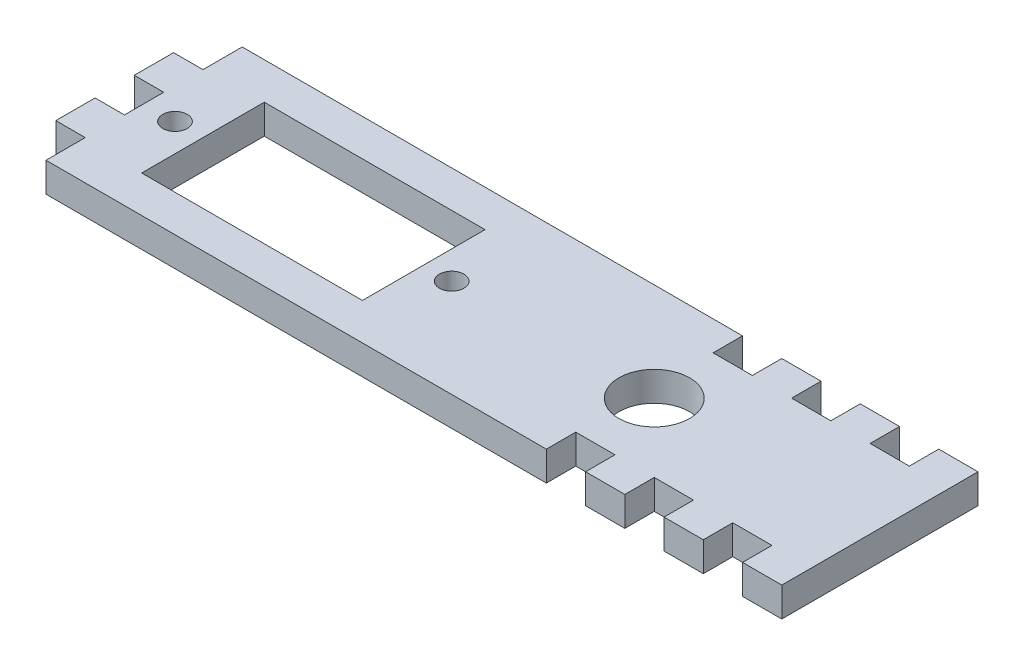
SolidWorks part; units mm, degrees
ref_plane "Alzado" through (0, 0, 0) normal (0, 0, 1) x (1, 0, 0)
ref_plane "Planta" through (0, 0, 0) normal (0, 1, 0) x (1, 0, 0)
ref_plane "Vista lateral" through (0, 0, 0) normal (1, 0, 0) x (0, 0, -1)
sketch "Croquis1" plane through (0, 0, 0) normal (0, 1, 0) x (1, 0, 0)
  line L1 (-37.5, -10) -> (37.5, -10)
  line L2 (-37.5, -10) -> (-37.5, 10)
  line L3 (-37.5, 10) -> (37.5, 10)
  line L4 (37.5, -10) -> (37.5, 10)
  line L5 (-37.5, -10) -> (37.5, 10) construction
  line L6 (-37.5, 10) -> (37.5, -10) construction
  line L14 (-37.5, 2) -> (-37.5, 6)
  line L15 (-37.5, -6) -> (-40.5, -6)
  line L16 (-31.5, 6.25) -> (-9, 6.25)
  line L17 (-31.5, 6.25) -> (-31.5, -6.25)
  line L18 (-31.5, -6.25) -> (-9, -6.25)
  line L19 (-9, 6.25) -> (-9, -6.25)
  line L20 (-31.5, 6.25) -> (-9, -6.25) construction
  line L21 (-31.5, -6.25) -> (-9, 6.25) construction
  line L22 (-37.5, -6) -> (-37.5, -2)
  line L23 (-37.5, -2) -> (-40.5, -2)
  line L24 (-40.5, -6) -> (-40.5, -2)
  line L25 (-37.5, 2) -> (-40.5, 2)
  line L26 (-40.5, 2) -> (-40.5, 6)
  line L27 (-37.5, 6) -> (-40.5, 6)
  line L36 (25.5, -10) -> (25.5, -7)
  line L37 (33.5, -10) -> (29.5, -10)
  line L38 (33.5, -10) -> (33.5, -7)
  line L39 (33.5, -7) -> (29.5, -7)
  line L40 (29.5, -10) -> (29.5, -7)
  line L41 (25.5, -10) -> (21.5, -10)
  line L42 (21.5, -10) -> (21.5, -7)
  line L43 (25.5, -7) -> (21.5, -7)
  line L44 (17.5, -10) -> (17.5, -7)
  line L45 (17.5, -10) -> (13.5, -10)
  line L46 (13.5, -10) -> (13.5, -7)
  line L47 (17.5, -7) -> (13.5, -7)
  line L48 (0, 0) -> (9.9901, 0) construction
  line L49 (33.5, 7) -> (29.5, 7)
  line L50 (29.5, 10) -> (29.5, 7)
  line L51 (33.5, 10) -> (29.5, 10)
  line L52 (33.5, 10) -> (33.5, 7)
  line L53 (25.5, 10) -> (21.5, 10)
  line L54 (21.5, 10) -> (21.5, 7)
  line L55 (25.5, 7) -> (21.5, 7)
  line L56 (25.5, 10) -> (25.5, 7)
  line L57 (17.5, 10) -> (13.5, 10)
  line L58 (13.5, 10) -> (13.5, 7)
  line L59 (17.5, 7) -> (13.5, 7)
  line L60 (17.5, 10) -> (17.5, 7)
  circle A0 centre (14.5, 0) radius 3.6
  circle A1 centre (-6.15, 0) radius 1.25
  circle A2 centre (-34.35, 0) radius 1.25
  point P0 (0, 0)
  point P16 (-20.25, 0)
  dimension "D3" = 7.2
  dimension "D5" = 2.5
  dimension "D11" = 4
  dimension "D1" = 75
  dimension "D2" = 20
  dimension "D4" = 14.5
  dimension "D7" = 28.2
  dimension "D8" = 22.5
  dimension "D9" = 12.5
  dimension "D10" = 20.25
  dimension "D6" = 14.1
  dimension "D12" = 4
  dimension "D14" = 3
  dimension "D15" = 4
  dimension "D16" = 23
  dimension "D20" = 3
  dimension "D21" = 4
  dimension "D22" = 4
  dimension "D25" = 4
  dimension "D13" = 2
  dimension "D23" = 3
extrude "Saliente-Extruir1" add sketch "Croquis1" along normal blind 3 contours L3 L60 L59 L58 L2 L1 L46 L47 L44 L42 L43 L36 L40 L39 L38 L4 L52 L49 L50 L56 L55 L54 A2 A1 A0 L16 L19 L18 L17 | L24 L15 L2 L23 | L2 L27 L26 L25
